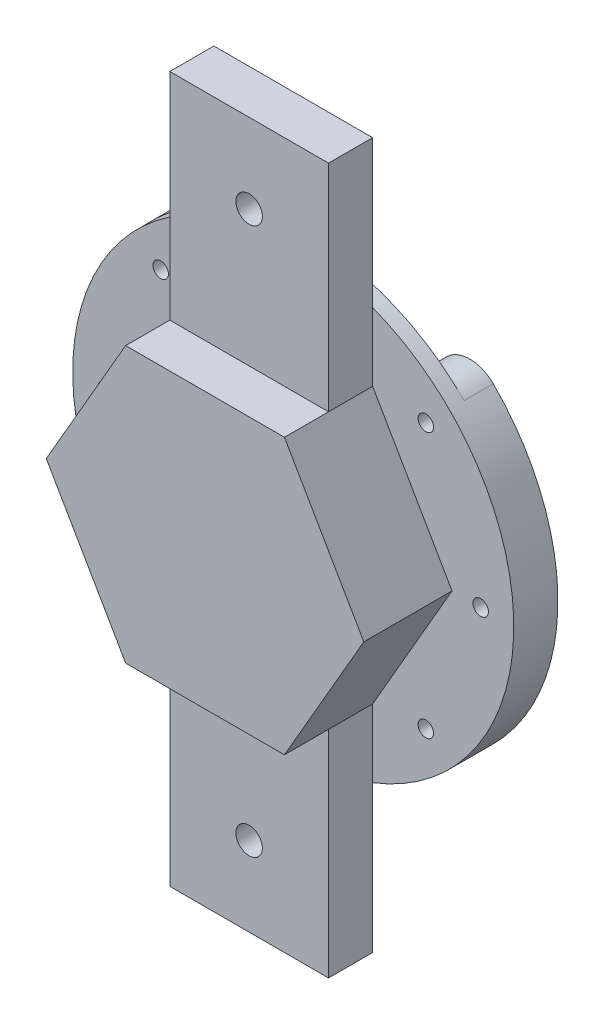
SolidWorks part; units mm, degrees
ref_plane "前视基准面" through (0, 0, 0) normal (0, 0, 1) x (1, 0, 0)
ref_plane "上视基准面" through (0, 0, 0) normal (0, 1, 0) x (1, 0, 0)
ref_plane "右视基准面" through (0, 0, 0) normal (1, 0, 0) x (0, 0, -1)
sketch "草图1" plane through (0, 0, 0) normal (0, 0, 1) x (1, 0, 0)
  line L0 (20.5061, -20.5061) -> (24.7487, -24.7487)
  line L1 (28.8675, -50) -> (57.735, 0)
  line L2 (57.735, 0) -> (28.8675, 50)
  line L3 (28.8675, 50) -> (-28.8675, 50)
  line L4 (-28.8675, 50) -> (-57.735, 0)
  line L5 (-57.735, 0) -> (-28.8675, -50)
  line L6 (-28.8675, -50) -> (28.8675, -50)
  line L7 (24.7487, 24.7487) -> (20.5061, 20.5061)
  line L8 (-24.7487, 24.7487) -> (-20.5061, 20.5061)
  line L9 (-20.5061, -20.5061) -> (-24.7487, -24.7487)
  line L10 (-24.7487, 24.7487) -> (-35.3553, 35.3553)
  line L11 (-35.3553, 35.3553) -> (-20.5061, 20.5061)
  line L12 (-20.5061, -20.5061) -> (-35.3553, -35.3553)
  line L13 (-35.3553, -35.3553) -> (-20.5061, -20.5061)
  line L14 (20.5061, 20.5061) -> (35.3553, 35.3553)
  line L15 (20.5061, -20.5061) -> (30.052, -30.052)
  line L16 (30.052, -30.052) -> (35.3553, -35.3553)
  arc A0 (-35.3553, 35.3553) -> (0, 50) centre (0, 0) ccw construction
  arc A1 (-1.7496, -42.464) -> (1.7496, -42.464) centre (0, 0) ccw
  arc A3 (-20.5061, 20.5061) -> (-20.5061, -20.5061) centre (0, 0) ccw
  circle A4 centre (-42.5, 0) radius 1.75
  circle A5 centre (-30.052, 30.052) radius 1.75
  circle A6 centre (0, 42.5) radius 1.75
  circle A7 centre (30.052, 30.052) radius 1.75
  circle A8 centre (42.5, 0) radius 1.75
  circle A9 centre (30.052, -30.052) radius 1.75
  circle A10 centre (0, -42.5) radius 1.75
  circle A11 centre (-30.052, -30.052) radius 1.75
  arc A12 (20.5061, -20.5061) -> (20.5061, 20.5061) centre (0, 0) ccw
  arc A13 (-35.3553, 35.3553) -> (35.3553, 35.3553) centre (0, 0) ccw
  arc A14 (1.7496, 42.464) -> (-1.7496, 42.464) centre (0, 0) ccw
  arc A15 (30.052, -30.052) -> (28.7894, 31.2637) centre (0, 0) ccw
  arc A16 (-28.7894, 31.2637) -> (-28.7894, -31.2637) centre (0, 0) ccw
  arc A17 (35.3553, 35.3553) -> (24.7487, 24.7487) centre (30.052, 30.052) ccw
  arc A18 (-35.3553, 35.3553) -> (-24.7487, 24.7487) centre (-30.052, 30.052) cw
  arc A19 (-24.7487, -24.7487) -> (-35.3553, -35.3553) centre (-30.052, -30.052) cw
  arc A20 (24.7487, -24.7487) -> (35.3553, -35.3553) centre (30.052, -30.052) ccw
  point P1 (0, 50)
  point P32 (0, 0)
  dimension "D1" = 100
  dimension "D2" = 8
extrude "凸台-拉伸1" add sketch "草图1" along normal blind 6.6 contours L14 A17 A7 | A15 A8 A9 L16 A13 L14 A7 | A8 A15 A7 L14 L7 A12 L0 L15 A9 | L15 A20 L16 A9 | A19 L12 A11 | A5 A16 A4 A11 L12 L9 A3 L8 L10 | A16 A5 L10 A13 L12 A11 A4 | A18 L10 A5
sketch "草图2" plane through (0, 0, 6.6) normal (0, 0, 1) x (1, 0, 0)
  circle A0 centre (0, 0) radius 50
extrude "凸台-拉伸2" add sketch "草图2" along normal blind 3.4
sketch "草图4" plane through (0, 0, 6.6) normal (0, 0, -1) x (-1, 0, 0)
  circle A0 centre (-42.5, 0) radius 1.75
  circle A1 centre (-30.052, 30.052) radius 1.75
  circle A2 centre (0, 42.5) radius 1.75
  circle A3 centre (30.052, 30.052) radius 1.75
  circle A4 centre (42.5, 0) radius 1.75
  circle A5 centre (30.052, -30.052) radius 1.75
  circle A6 centre (0, -42.5) radius 1.75
  circle A7 centre (-30.052, -30.052) radius 1.75
  point P20 (0, 0)
  dimension "D1" = 8
extrude "切除-拉伸2" cut sketch "草图4" against normal mid plane 20 contours A0 | A1 | A7 | A5 | A4 | A3
sketch "草图5" plane through (0, 0, 10) normal (0, 0, 1) x (1, 0, 0)
  line L0 (-18, -31.1769) -> (-18, -80)
  line L1 (36, 0) -> (18, 31.1769)
  line L3 (-18, 31.1769) -> (-36, 0)
  line L4 (-36, 0) -> (-18, -31.1769)
  line L6 (18, -31.1769) -> (36, 0)
  line L7 (-18, 80) -> (18, 80)
  line L8 (-18, 80) -> (-18, 31.1769)
  line L9 (-18, -80) -> (18, -80)
  line L10 (18, 80) -> (18, 31.1769)
  line L13 (18, -31.1769) -> (18, -80)
  line L16 (18, 31.1769) -> (-18, 31.1769) [skipped]
  line L17 (7.0148, -31.1769) -> (18, -31.1769) [skipped]
  dimension "D1" = 160
extrude "凸台-拉伸7" add sketch "草图5" along normal blind 20
sketch "草图10" plane through (0, 0, 30) normal (0, 0, 1) x (1, 0, 0)
  line L0 (-18, -31.1769) -> (-18, -80)
  line L1 (-18, 80) -> (18, 80)
  line L2 (-18, 80) -> (-18, 31.1769)
  line L3 (-18, -80) -> (18, -80)
  line L4 (18, 80) -> (18, 31.1769)
  line L8 (18, 31.1769) -> (-18, 31.1769)
  line L11 (-18, -31.1769) -> (18, -31.1769)
  line L15 (18, -31.1769) -> (18, -80)
  line L16 (18, -31.1769) -> (27, -15.5885) [skipped]
  line L17 (-36, 0) -> (-27, -15.5885) [skipped]
  line L18 (-18, 31.1769) -> (-27, 15.5885) [skipped]
  line L19 (27, 15.5885) -> (18, 31.1769) [skipped]
  point P0 (0, 0)
extrude "切除-拉伸3" cut sketch "草图10" against normal blind 10
sketch "草图11" plane through (0, 0, 20) normal (0, 0, 1) x (1, 0, 0)
  line L0 (18, 80) -> (-18, 80) construction
  circle A0 centre (0, 62) radius 3
  dimension "D2" = 6
  dimension "D1" = 18
extrude "切除-拉伸6" cut sketch "草图11" against normal blind 10 contours A0
mirror "镜向2" about plane through (0, 0, 0) normal (0, 1, 0) of "切除-拉伸6"
